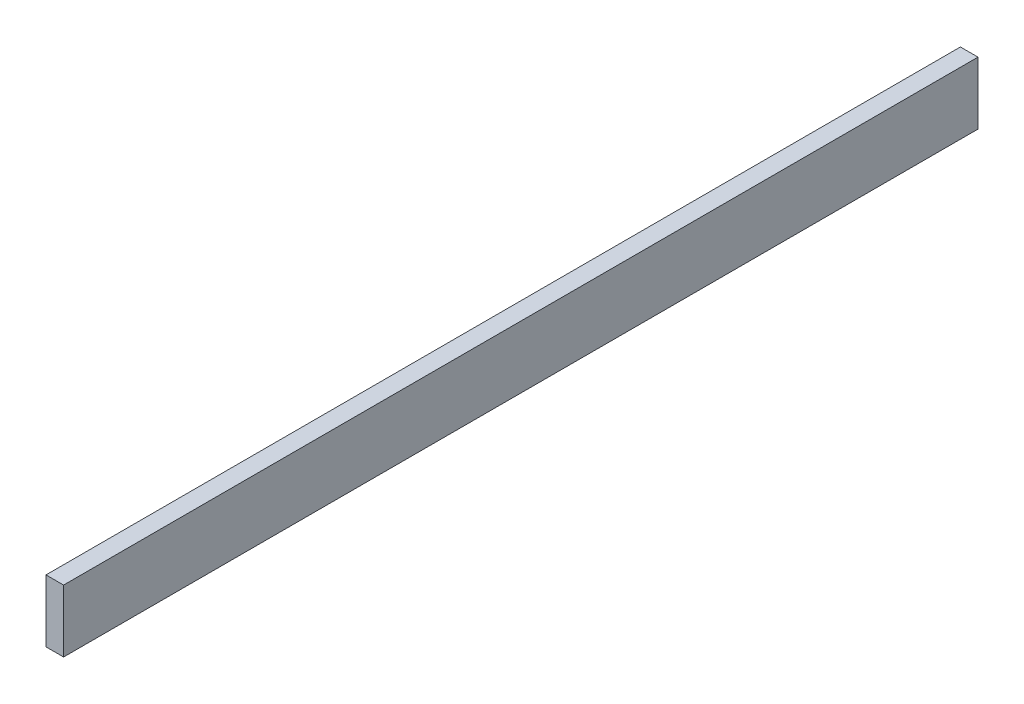
SolidWorks part; units mm, degrees
ref_plane "Front Plane" through (0, 0, 0) normal (0, 0, 1) x (1, 0, 0)
ref_plane "Top Plane" through (0, 0, 0) normal (0, 1, 0) x (1, 0, 0)
ref_plane "Right Plane" through (0, 0, 0) normal (1, 0, 0) x (0, 0, -1)
other "Configuration Table"
sketch "Sketch1" plane through (0, 0, 0) normal (0, 0, 1) x (1, 0, 0)
  line L1 (0, 18) -> (12.7, 18)
  line L2 (0, 18) -> (0, 63)
  line L3 (0, 63) -> (12.7, 63)
  line L4 (12.7, 18) -> (12.7, 63)
extrude "CEK_donmus_ray_ic_profil_sol_1" add sketch "Sketch1" against normal blind 660 separate body
